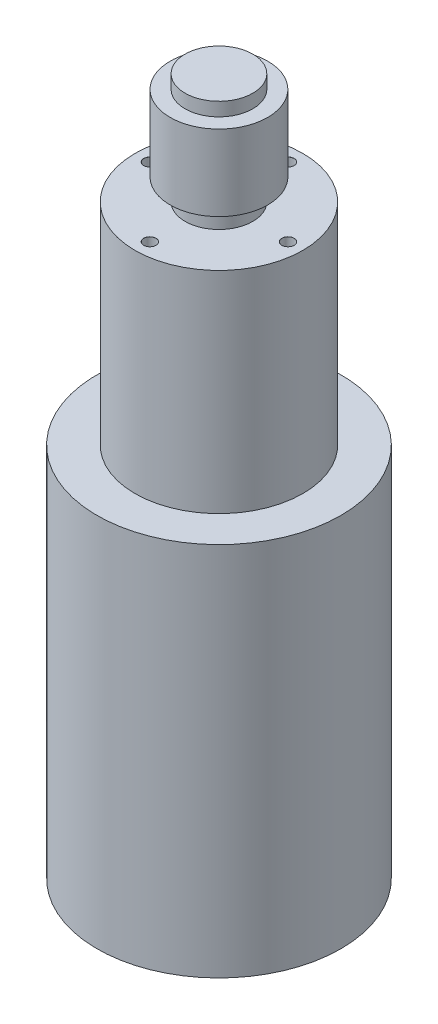
SolidWorks part; units mm, degrees
material "Acciaio al carbonio semplice"
ref_plane "Piano frontale" through (0, 0, 0) normal (0, 0, 1) x (1, 0, 0)
ref_plane "Piano superiore" through (0, 0, 0) normal (0, 1, 0) x (1, 0, 0)
ref_plane "Piano destro" through (0, 0, 0) normal (1, 0, 0) x (0, 0, -1)
sketch "Schizzo2" plane through (0, 0, 0) normal (0, 0, 1) x (1, 0, 0)
  line L0 (0, -1182.3942) -> (0, 57937.316) construction
  line L1 (0, 257.3) -> (12.5, 257.3)
  line L2 (12.5, 257.3) -> (12.5, 252.3)
  line L3 (12.5, 252.3) -> (18, 252.3)
  line L4 (18, 252.3) -> (18, 224.3)
  line L5 (18, 224.3) -> (12.5, 224.3)
  line L6 (12.5, 224.3) -> (12.5, 216.3)
  line L7 (12.5, 216.3) -> (31, 216.3)
  line L8 (31, 216.3) -> (31, 138.55)
  line L9 (31, 138.55) -> (45, 138.55)
  line L10 (45, 138.55) -> (45, 0)
  line L11 (45, 0) -> (0, 0)
  line L12 (0, 257.3) -> (0, 0)
  point P5 (31, 177.425)
  point P16 (0, 0)
  point P17 (15.5449, 216.3)
  dimension "D1" = 45
  dimension "D2" = 138.55
  dimension "D3" = 31
  dimension "D4" = 8
  dimension "D5" = 77.75
  dimension "D6" = 12.5
  dimension "D7" = 33
  dimension "D8" = 5
  dimension "D9" = 18
revolve "Rivoluzione1" add sketch "Schizzo2" angle 360 about L0
hole_wizard "Foro per Vite M4-1" positions "Schizzo7" profile "Schizzo6" hole size "M4" standard "ISO"
sketch "Schizzo7" plane through (0, 216.3, 0) normal (0, 1, 0) x (1, 0, 0)
  point P0 (0, 25.5)
  point P2 (25.5, 0)
  point P4 (0, -25.5)
  point P6 (-25.5, 0)
  point P9 (0, 0)
  point P11 (0, 0)
  point P12 (0, 0)
  point P13 (0, 0)
  point P22 (0, 0)
  dimension "D1" = 25.5
  dimension "D2" = 25.5
  dimension "D3" = 25.5
  dimension "D4" = 25.5
sketch "Schizzo6" plane through (0, 216.3, -25.5) normal (1, 0, 0) x (0, 0, 1)
  line L0 (0, 0) -> (0, 18.3519)
  line L1 (0, 18.3519) -> (2.25, 17)
  line L2 (2.25, 17) -> (2.25, 0.025)
  line L3 (2.25, 0.025) -> (2.275, 0)
  line L5 (2.275, 0) -> (0, 0)
  line L6 (-2.25, 0.025) -> (-2.275, 0) construction
  line L10 (0, 18.3519) -> (-2.25, 17) construction
  line L11 (0, -6.35) -> (0, 107.95) construction
  dimension "Hole Dia." = 4.5
  dimension "Hole Depth" = 17
  dimension "Near C'Sink Dia." = 4.55
  dimension "Near C'Sink Angle" = 90
  dimension "Drill Angle" = 118
